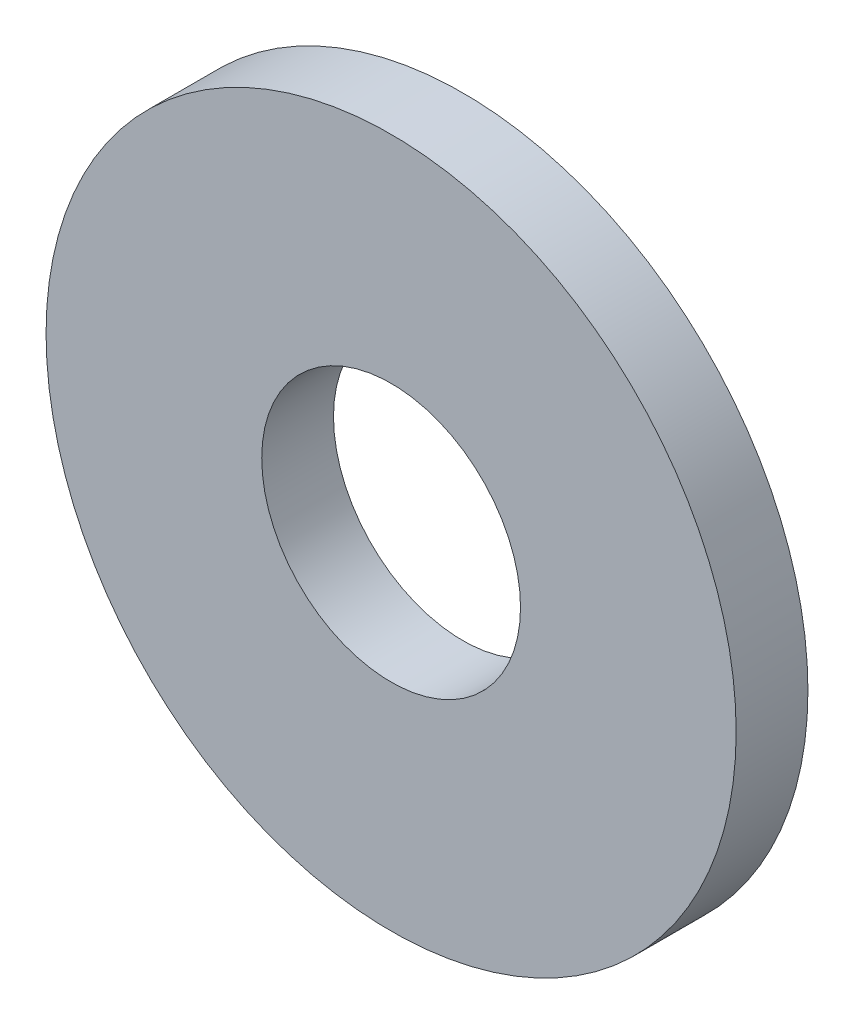
SolidWorks part; units mm, degrees
ref_plane "Front Plane" through (0, 0, 0) normal (0, 0, 1) x (1, 0, 0)
ref_plane "Top Plane" through (0, 0, 0) normal (0, 1, 0) x (1, 0, 0)
ref_plane "Right Plane" through (0, 0, 0) normal (1, 0, 0) x (0, 0, -1)
sketch "Sketch2" plane through (0, 0, 0) normal (0, 0, 1) x (1, 0, 0)
  circle A0 centre (0, 0) radius 12.7
  circle A1 centre (0, 0) radius 4.7625
  dimension "D1" = 25.4
  dimension "D2" = 9.525
extrude "Boss-Extrude1" add sketch "Sketch2" along normal mid plane 2.6416
